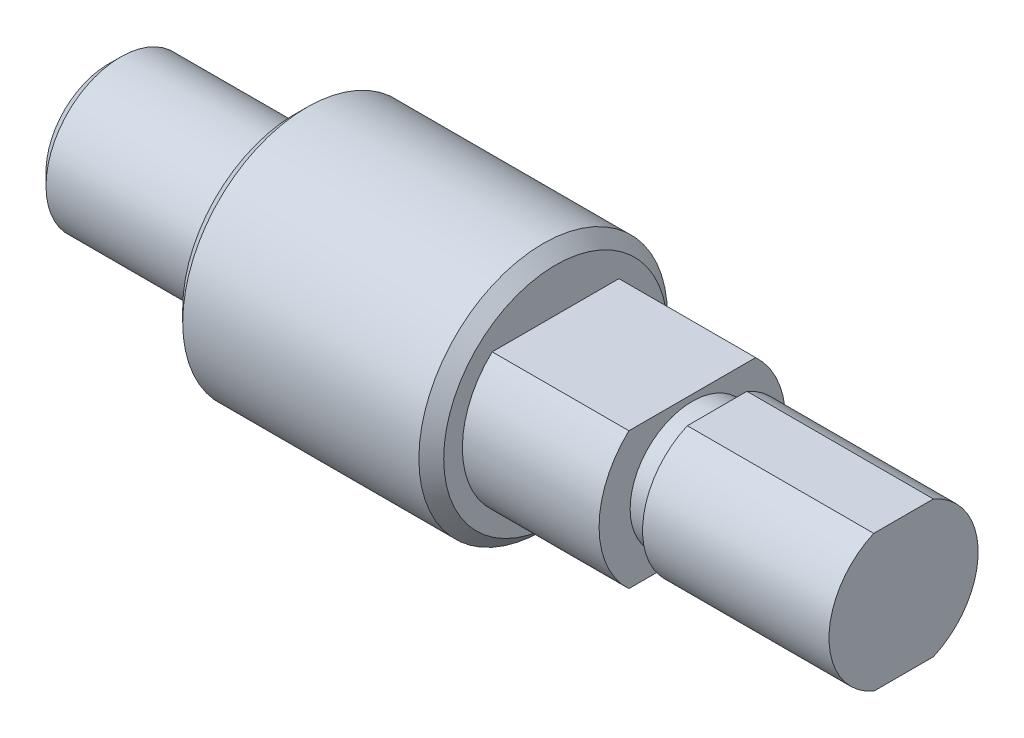
SolidWorks part; units mm, degrees
ref_plane "前视基准面" through (0, 0, 0) normal (0, 0, 1) x (1, 0, 0)
ref_plane "上视基准面" through (0, 0, 0) normal (0, 1, 0) x (1, 0, 0)
ref_plane "右视基准面" through (0, 0, 0) normal (1, 0, 0) x (0, 0, -1)
sketch "草图1" plane through (0, 0, 0) normal (0, 0, 1) x (1, 0, 0)
  line L0 (1180.7086, 1047.3774) -> (1249.1117, 1047.3774) construction
  line L1 (1183.1227, 1053.3774) -> (1198.1227, 1053.3774)
  line L2 (1219.1227, 1054.8774) -> (1230.1227, 1054.8774)
  line L3 (1230.1227, 1052.3774) -> (1232.1227, 1052.3774)
  line L5 (1183.1227, 1049.8774) -> (1196.0626, 1049.8774)
  line L6 (1196.0626, 1049.8774) -> (1199.8353, 1047.3774)
  line L7 (1199.8353, 1047.3774) -> (1247.1227, 1047.3774)
  line L49 (1247.1227, 1053.3774) -> (1247.1227, 1047.3774)
  line L53 (1198.1227, 1056.3774) -> (1198.1227, 1053.3774)
  line L54 (1219.1227, 1056.3774) -> (1219.1227, 1054.8774)
  line L57 (1230.1227, 1054.8774) -> (1230.1227, 1052.3774)
  line L59 (1218.1227, 1057.3774) -> (1199.1227, 1057.3774)
  line L64 (1232.1227, 1053.3774) -> (1232.1227, 1052.3774)
  line L65 (1232.1227, 1053.3774) -> (1247.1227, 1053.3774)
  line L75 (1219.1227, 1056.3774) -> (1218.1227, 1057.3774)
  line L76 (1199.1227, 1057.3774) -> (1198.1227, 1056.3774)
  line L83 (1183.1227, 1053.3774) -> (1183.1227, 1049.8774)
  dimension "D1" = 2.5
  dimension "D2" = 6
  dimension "D3" = 64
  dimension "D4" = 7.5
  dimension "D5" = 10
  dimension "D6" = 5
revolve "旋转6" add sketch "草图1" angle 360 about L0
chamfer "倒角1" distance 1 angle 45 1 edges at (1183.1227, 1047.3774, 6)
sketch "草图3" plane through (1183.1227, 0, 0) normal (-1, 0, 0) x (0, 0, 1)
  circle A0 centre (0, 1047.3774) radius 5
sketch "草图6" plane through (0, 0, 0) normal (0, 0, 1) x (1, 0, 0)
  line L0 (1183.1227, 1047.3774) -> (1253.5921, 1047.3774) construction
  line L1 (1183.1227, 1052.3774) -> (1183.1227, 1042.3774) construction
  line L2 (1251.2854, 1052.8774) -> (1219.1227, 1052.8774)
  line L3 (1219.1227, 1038.3774) -> (1219.1227, 1056.3774) construction
  line L4 (1219.1227, 1052.8774) -> (1219.1227, 1059.114)
  line L5 (1219.1227, 1059.114) -> (1251.2854, 1059.114)
  line L6 (1251.2854, 1059.114) -> (1251.2854, 1052.8774)
  line L7 (1251.2854, 1041.8774) -> (1219.1227, 1041.8774)
  line L8 (1251.2854, 1035.6409) -> (1251.2854, 1041.8774)
  line L9 (1219.1227, 1041.8774) -> (1219.1227, 1035.6409)
  line L10 (1219.1227, 1035.6409) -> (1251.2854, 1035.6409)
  dimension "D1" = 5.5
extrude "拉伸1" cut sketch "草图6" against normal mid plane 50
